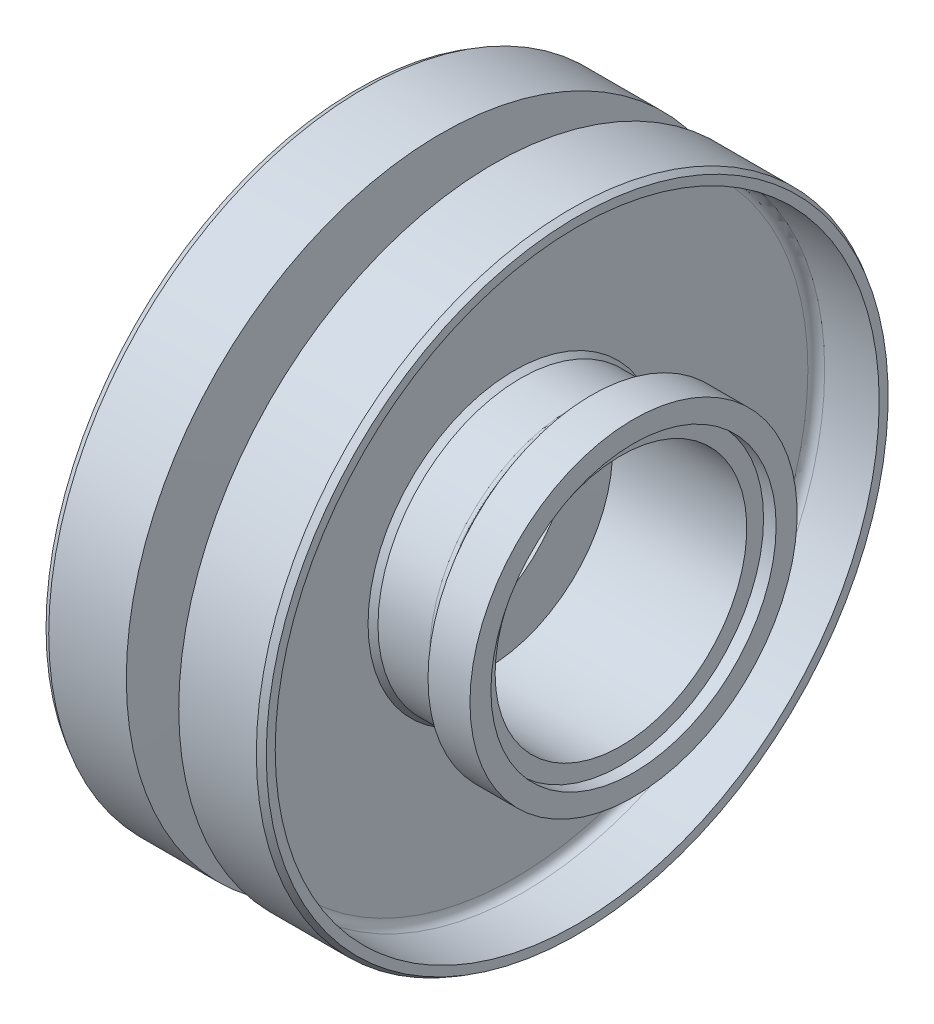
SolidWorks part; units mm, degrees
ref_plane "Plan de face" through (0, 0, 0) normal (0, 0, 1) x (1, 0, 0)
ref_plane "Plan de dessus" through (0, 0, 0) normal (0, 1, 0) x (1, 0, 0)
ref_plane "Plan de droite" through (0, 0, 0) normal (1, 0, 0) x (0, 0, -1)
sketch "Esquisse1" plane through (0, 0, 0) normal (0, 0, 1) x (1, 0, 0)
  line L1 (6.25, 75) -> (24.75, 75)
  line L2 (24.75, 75) -> (26.25, 74.134)
  line L3 (26.25, 74.134) -> (26.25, 72)
  line L4 (26.25, 72) -> (13.25, 72)
  line L7 (12.75, 34) -> (25.0553, 34)
  line L8 (26.6786, 34.8317) -> (29.6786, 39)
  line L10 (29.6786, 39) -> (39.6786, 39)
  line L12 (39.6786, 39) -> (39.6786, 34)
  line L13 (39.6786, 34) -> (36.6786, 34)
  line L14 (36.6786, 34) -> (36.6786, 30)
  line L15 (36.6786, 30) -> (4.6786, 30)
  line L16 (0, 0) -> (0, 83.5945) construction
  line L17 (0, 0) -> (102.1775, 0) construction
  line L18 (6.25, 75) -> (4.6786, 30)
  line L19 (11.25, 70) -> (11.25, 34.866)
  line L20 (11.25, 34.866) -> (12.75, 34)
  line L21 (-11.25, 34.866) -> (-12.75, 34)
  line L22 (-11.25, 70) -> (-11.25, 34.866)
  line L23 (-6.25, 75) -> (-4.6786, 30)
  line L24 (-36.6786, 30) -> (-4.6786, 30)
  line L25 (-36.6786, 34) -> (-36.6786, 30)
  line L26 (-39.6786, 34) -> (-36.6786, 34)
  line L27 (-39.6786, 39) -> (-39.6786, 34)
  line L28 (-29.6786, 39) -> (-39.6786, 39)
  line L29 (-26.6786, 34.8317) -> (-29.6786, 39)
  line L30 (-12.75, 34) -> (-25.0553, 34)
  line L31 (-26.25, 72) -> (-13.25, 72)
  line L32 (-26.25, 74.134) -> (-26.25, 72)
  line L33 (-24.75, 75) -> (-26.25, 74.134)
  line L34 (-6.25, 75) -> (-24.75, 75)
  arc A0 (13.25, 72) -> (11.25, 70) centre (13.25, 70) ccw
  arc A1 (25.0553, 34) -> (26.6786, 34.8317) centre (25.0553, 36) ccw
  arc A2 (-25.0553, 34) -> (-26.6786, 34.8317) centre (-25.0553, 36) cw
  arc A3 (-13.25, 72) -> (-11.25, 70) centre (-13.25, 70) cw
  dimension "D8" = 2
  dimension "D1" = 150
  dimension "D2" = 12.5
  dimension "D3" = 2
  dimension "D4" = 3
  dimension "D5" = 10
  dimension "D6" = 35
  dimension "D7" = 4
  dimension "D9" = 3
  dimension "D10" = 20
  dimension "D11" = 5
  dimension "D12" = 30
  dimension "D13" = 5
  dimension "D14" = 1.5
  dimension "D15" = 15
  dimension "D16" = 3
  dimension "D17" = 30
revolve "Révolution1" add sketch "Esquisse1" angle 360 about L17
